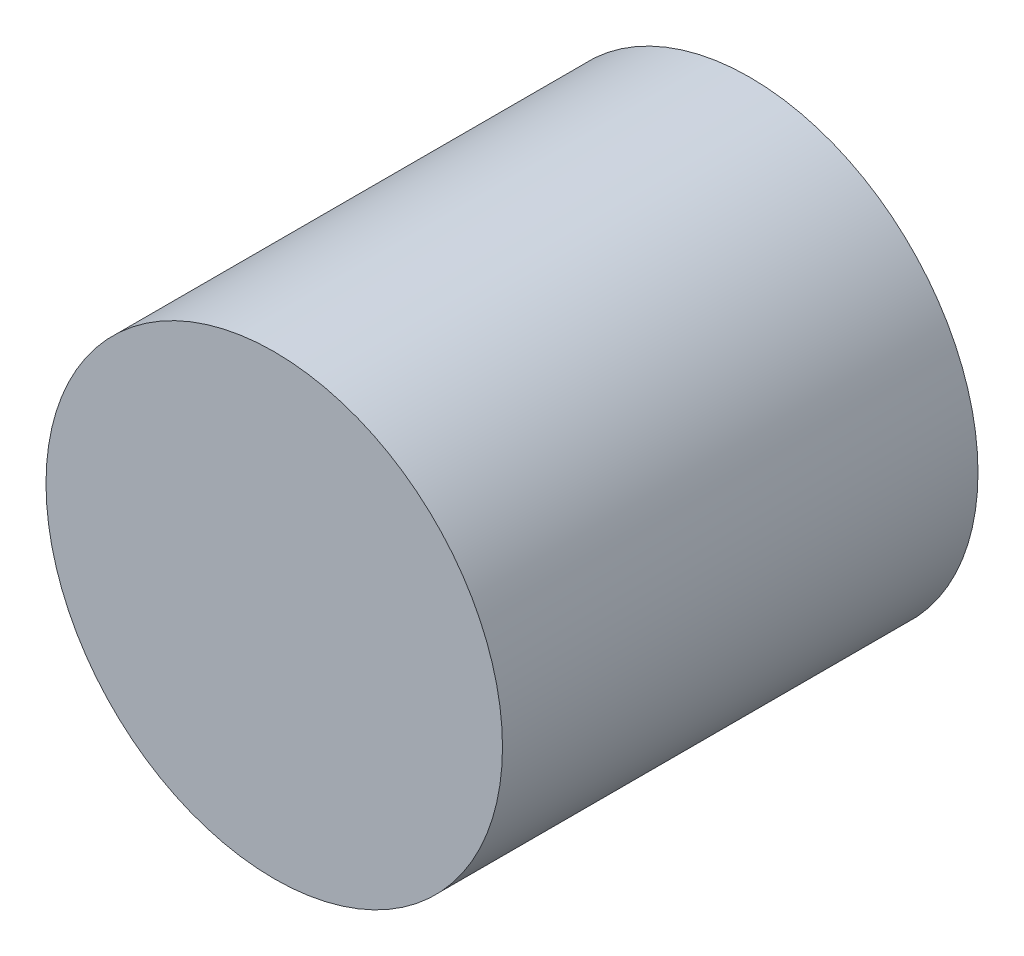
SolidWorks part; units mm, degrees
ref_plane "Alzado" through (0, 0, 0) normal (0, 0, 1) x (1, 0, 0)
ref_plane "Planta" through (0, 0, 0) normal (0, 1, 0) x (1, 0, 0)
ref_plane "Vista lateral" through (0, 0, 0) normal (1, 0, 0) x (0, 0, -1)
sketch "Croquis1" plane through (0, 0, 0) normal (0, 0, 1) x (1, 0, 0)
  circle A0 centre (0, 0) radius 24
  dimension "D1" = 48
extrude "Saliente-Extruir1" add sketch "Croquis1" along normal blind 50
sketch "Croquis2" plane through (0, 0, 0) normal (0, 0, -1) x (-1, 0, 0)
  circle A0 centre (0, 0) radius 5
  dimension "D1" = 10
extrude "Cortar-Extruir1" cut sketch "Croquis2" against normal blind 10
